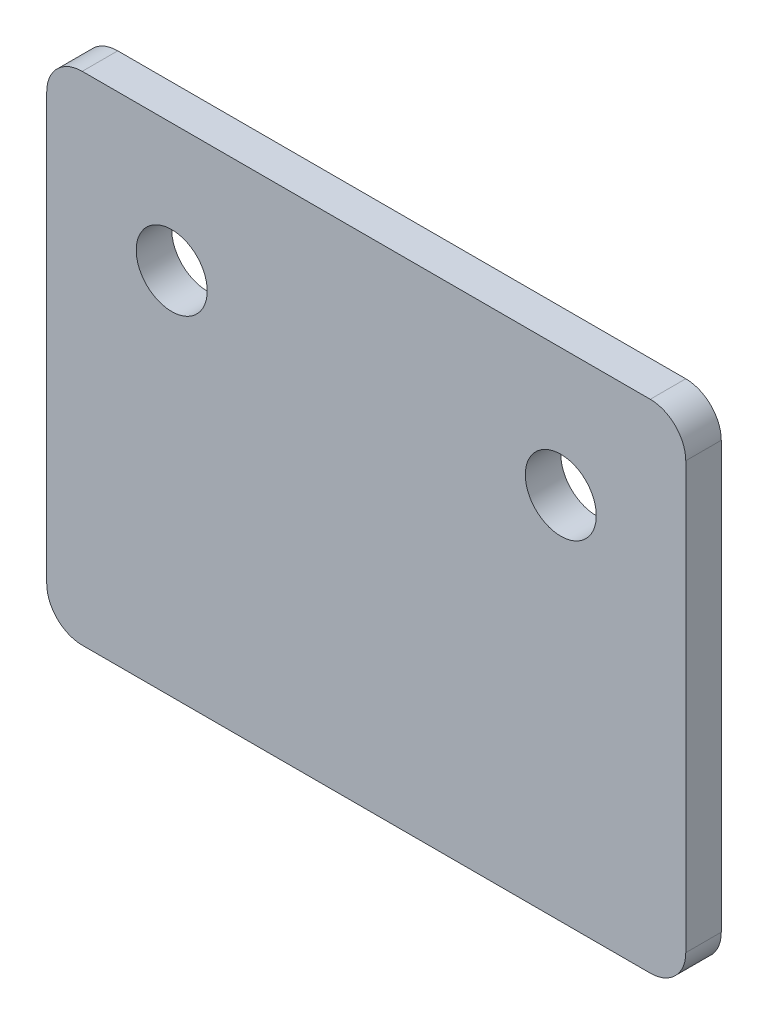
SolidWorks part; units mm, degrees
material "AISI 4130 Steel, annealed at 865C"
ref_plane "X-Y Datum" through (0, 0, 0) normal (0, 0, 1) x (1, 0, 0)
ref_plane "X-Z Datum" through (0, 0, 0) normal (0, 1, 0) x (1, 0, 0)
ref_plane "Y-Z Datum" through (0, 0, 0) normal (1, 0, 0) x (0, 0, -1)
sketch "Sketch1" plane through (0, 0, 0) normal (0, 0, 1) x (1, 0, 0)
  line L1 (-28.329, 3.0708) -> (-28.329, -35.0292)
  line L2 (-25.154, -38.2042) -> (25.646, -38.2042)
  line L3 (28.821, -35.0292) -> (28.821, 3.0708)
  line L4 (-25.154, 6.2458) -> (25.646, 6.2458)
  arc A0 (-28.329, -35.0292) -> (-25.154, -38.2042) centre (-25.154, -35.0292) ccw
  arc A1 (28.821, -35.0292) -> (25.646, -38.2042) centre (25.646, -35.0292) cw
  arc A2 (25.646, 6.2458) -> (28.821, 3.0708) centre (25.646, 3.0708) cw
  arc A3 (-25.154, 6.2458) -> (-28.329, 3.0708) centre (-25.154, 3.0708) ccw
  point P4 (0, 0)
  dimension "D1" = 3.175
  dimension "D2" = 57.15
  dimension "D3" = 44.45
extrude "Boss-Extrude1" add sketch "Sketch1" against normal blind 3.175
sketch "Sketch2" plane through (0, 0, 0) normal (0, 0, 1) x (1, 0, 0)
  line L0 (0.246, -38.2042) -> (0.246, 6.2458) construction
  line L1 (-25.154, -38.2042) -> (25.646, -38.2042) construction
  line L3 (-17.153, -5.1842) -> (-17.153, 6.2458) construction
  line L4 (25.646, 6.2458) -> (-25.154, 6.2458) construction
  line L5 (-28.329, -5.1842) -> (-17.153, -5.1842) construction
  line L6 (-28.329, 3.0708) -> (-28.329, -35.0292) construction
  circle A0 centre (-17.153, -5.1842) radius 3.175
  circle A1 centre (17.645, -5.1842) radius 3.175
  dimension "D1" = 11.176
  dimension "D3" = 6.35
  dimension "D2" = 11.43
extrude "Cut-Extrude1" cut sketch "Sketch2" against normal through all
